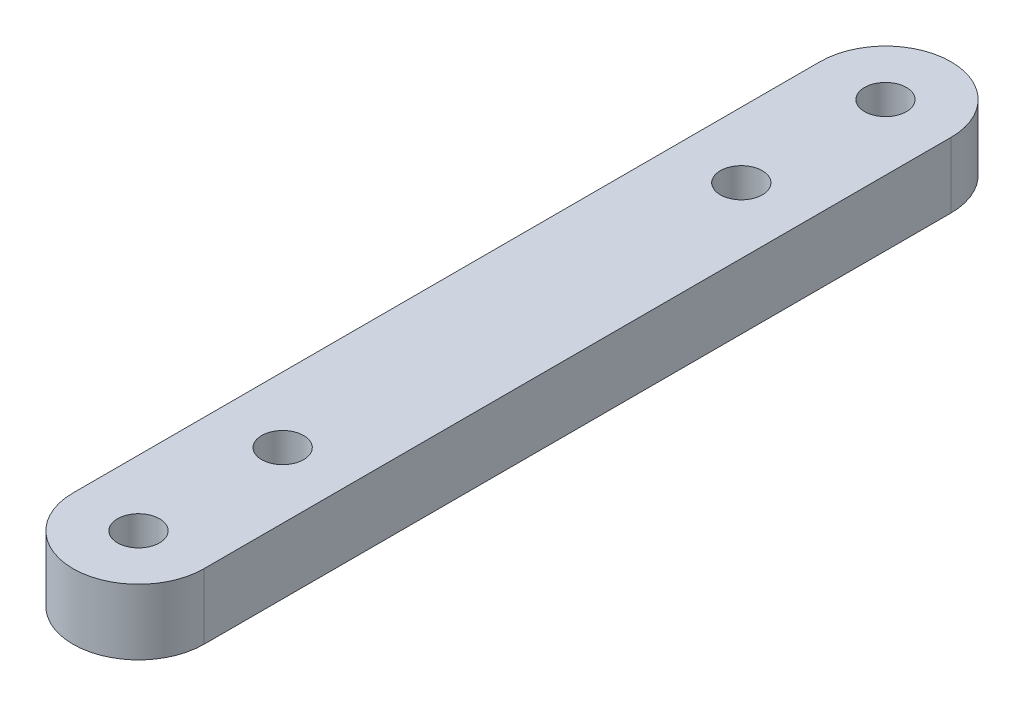
SolidWorks part; units mm, degrees
ref_plane "Ebene vorne" through (0, 0, 0) normal (0, 0, 1) x (1, 0, 0)
ref_plane "Ebene oben" through (0, 0, 0) normal (0, 1, 0) x (1, 0, 0)
ref_plane "Ebene rechts" through (0, 0, 0) normal (1, 0, 0) x (0, 0, -1)
sketch "Skizze2" plane through (0, 0, 0) normal (0, 1, 0) x (1, 0, 0)
  line L0 (-4, 28.5) -> (-4, -28.5)
  line L1 (6, 28.5) -> (6, -28.5)
  line L3 (6, 0) -> (20.8364, 0) construction
  circle A0 centre (1, 28.5) radius 1.6
  arc A1 (6, 28.5) -> (-4, 28.5) centre (1, 28.5) ccw
  circle A2 centre (1, 17.5) radius 1.6
  circle A3 centre (1, -17.5) radius 1.6
  arc A4 (6, -28.5) -> (-4, -28.5) centre (1, -28.5) cw
  circle A5 centre (1, -28.5) radius 1.6
  dimension "D1" = 3.2
  dimension "D2" = 10
  dimension "D3" = 3.2
  dimension "D5" = 5
  dimension "D4" = 17.5
extrude "Aufsatz-Linear austragen1" add sketch "Skizze2" along normal blind 5
sketch "Skizze3" plane through (0, 0, 0) normal (0, -1, 0) x (1, 0, 0)
  circle A0 centre (1, 17.5) radius 3
  circle A1 centre (1, -17.5) radius 3
  dimension "D1" = 6
  dimension "D2" = 6
extrude "Schnitt-Linear austragen1" cut sketch "Skizze3" against normal blind 2.5
